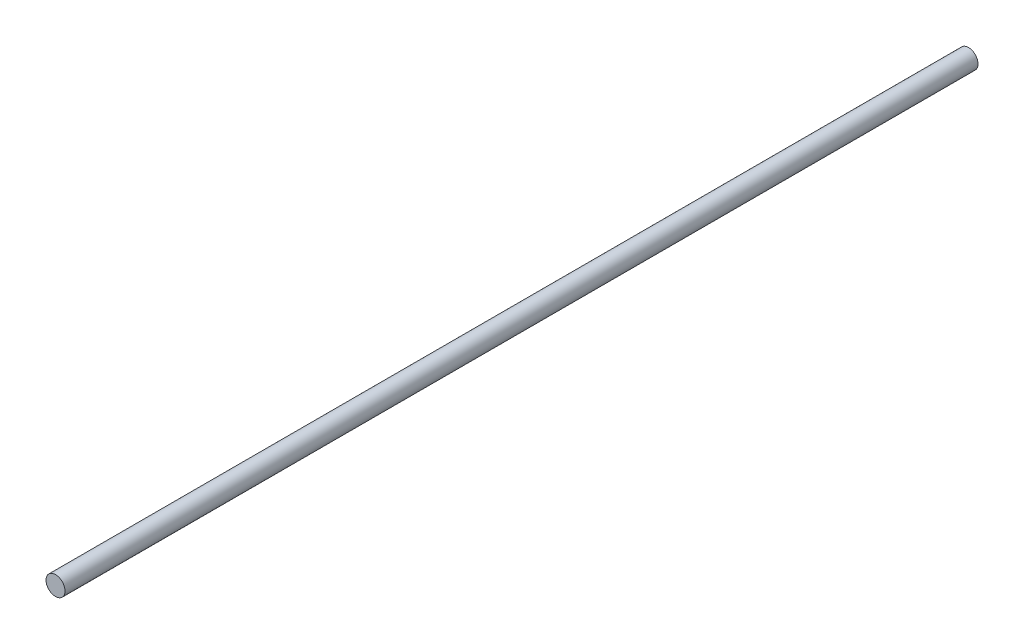
SolidWorks part; units mm, degrees
material "AISI 304"
ref_plane "Front" through (0, 0, 0) normal (0, 0, 1) x (1, 0, 0)
ref_plane "Top" through (0, 0, 0) normal (0, 1, 0) x (1, 0, 0)
ref_plane "Right" through (0, 0, 0) normal (1, 0, 0) x (0, 0, -1)
sketch "Sketch1" plane through (0, 0, 0) normal (0, 0, 1) x (1, 0, 0)
  circle A0 centre (0, 0) radius 3.175
  dimension "D1" = 6.35
extrude "Boss-Extrude1" add sketch "Sketch1" along normal mid plane 304.8
